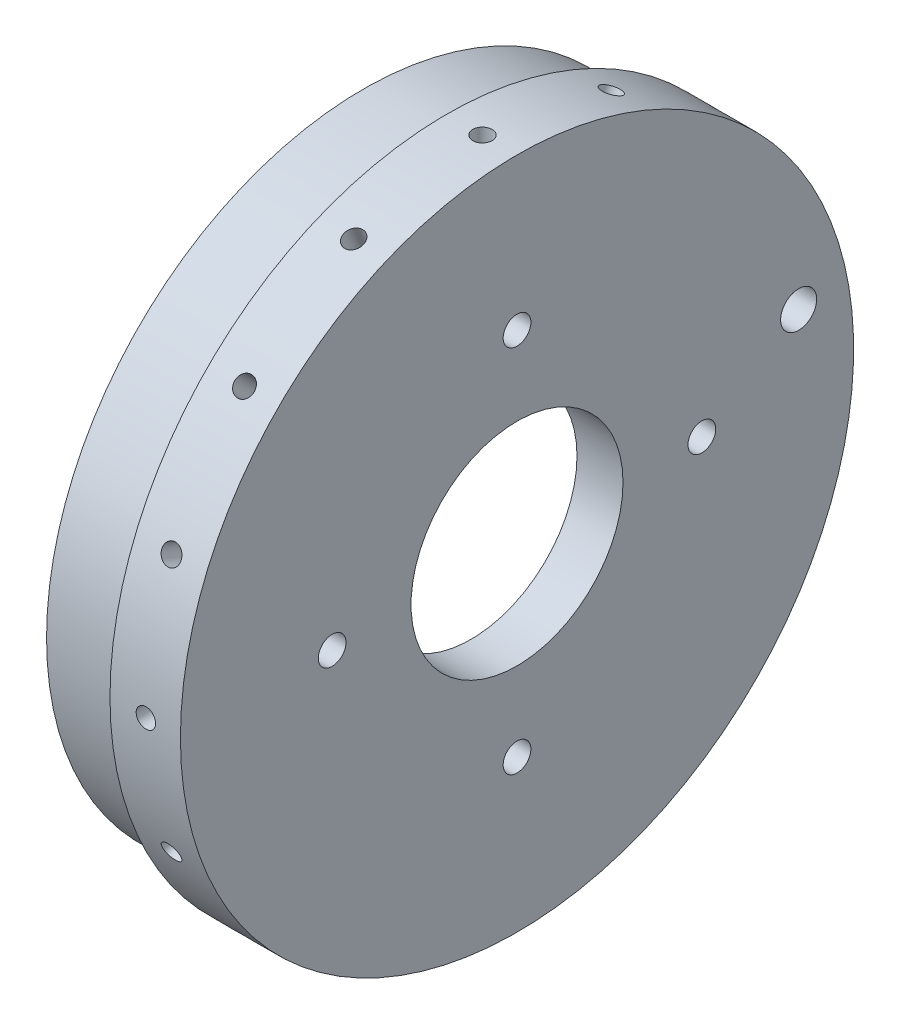
SolidWorks part; units mm, degrees
material "6061 Alloy"
ref_plane "Front Plane" through (0, 0, 0) normal (0, 0, 1) x (1, 0, 0)
ref_plane "Top Plane" through (0, 0, 0) normal (0, 1, 0) x (1, 0, 0)
ref_plane "Right Plane" through (0, 0, 0) normal (1, 0, 0) x (0, 0, -1)
sketch "Sketch4" plane through (0, 0, 0) normal (0, 0, 1) x (1, 0, 0)
  line L0 (0, 0) -> (0, 57.15)
  line L1 (0, 57.15) -> (34.225, 57.15)
  line L2 (34.225, 57.15) -> (34.225, 60.706)
  line L3 (34.225, 60.706) -> (46.925, 60.706)
  line L14 (46.925, 60.706) -> (46.925, 0)
  line L15 (0, 0) -> (46.925, 0)
  dimension "D2" = 34.225
  dimension "D5" = 12.7
  dimension "D6" = 57.15
  dimension "D1" = 60.706
revolve "Revolve1" add sketch "Sketch4" angle 360 about L15
hole_wizard "#6-32 Tapped Hole1" positions "3DSketch4" profile "Sketch5" tap size "#6-32" standard "ANSI Inch"
sketch3d "3DSketch4"
  line L0 (40.702, 0, 60.706) -> (46.925, 0, 60.706) construction
  line L2 (40.702, 0, 60.706) -> (34.225, 0, 60.706) construction
  circle A1 centre (46.925, 0, 0) radius 60.706 construction
  circle A2 centre (34.225, 0, 0) radius 60.706 construction
  point P10 (40.702, 0, 60.706)
  point P18 (-13.781, 0, 0)
  point P24 (-26.481, 0, 0)
  dimension "D1" = 6.477
sketch "Sketch5" plane through (40.702, 0, 60.706) normal (1, 0, 0) x (0, -1, 0)
  line L0 (0, 0) -> (0, 13.5127)
  line L1 (0, 13.5127) -> (1.3525, 12.7)
  line L2 (1.3525, 12.7) -> (1.3525, 10.16)
  line L3 (1.3525, 10.16) -> (1.7526, 10.16)
  line L4 (1.7526, 10.16) -> (1.7526, 0)
  line L5 (1.7526, 0) -> (0, 0)
  line L10 (0, 13.5127) -> (-1.3526, 12.7) construction
  line L11 (0, -6.35) -> (0, 107.95) construction
  dimension "Tap Drill Dia." = 2.7051
  dimension "Tap Drill Depth" = 12.7
  dimension "Thread Major Dia." = 3.5052
  dimension "Thread Depth" = 10.16
  dimension "Drill Angle" = 118
pattern_circular "CirPattern3" count 16 over 360 about axis through (0, 0, 0) along (1, 0, 0) of "#6-32 Tapped Hole1"
sketch "Sketch6" plane through (0, 0, 0) normal (-1, 0, 0) x (0, 0, 1)
  circle A0 centre (0, 0) radius 57.15
extrude "Cut-Extrude1" cut sketch "Sketch6" against normal blind 19.23 contours A0
sketch "Sketch7" plane through (46.925, 0, 0) normal (1, 0, 0) x (0, 0, -1)
  line L0 (16.805, -1010.8221) -> (16.805, 48989.1779) construction
  line L1 (16.805, 21.05) -> (-16.805, 21.05)
  line L2 (21.05, 16.805) -> (21.05, -16.805)
  line L3 (16.805, -21.05) -> (-16.805, -21.05)
  line L4 (-21.05, 16.805) -> (-21.05, -16.805)
  line L5 (21.05, 21.05) -> (-21.05, -21.05) construction
  line L6 (21.05, -21.05) -> (-21.05, 21.05) construction
  line L7 (0, -1000) -> (0, 49000) construction
  line L8 (-16.805, -1002.9393) -> (-16.805, 48997.0607) construction
  line L9 (-21.05, 0) -> (49000, 0) construction
  line L10 (-21.05, 16.805) -> (48969.2707, 16.805) construction
  line L12 (-21.05, 16.805) -> (-16.805, 21.05)
  line L13 (16.805, 21.05) -> (21.05, 16.805)
  line L14 (21.05, -16.805) -> (16.805, -21.05)
  line L15 (-16.805, -21.05) -> (-21.05, -16.805)
  point P0 (0, 0)
  point P30 (0, 0)
  dimension "D1" = 42.1
  dimension "D2" = 42.1
  dimension "D3" = 16.805
  dimension "D4" = 16.805
  dimension "D5" = 16.805
  dimension "D7" = 4
sketch "Sketch8" plane through (46.925, 0, 0) normal (1, 0, 0) x (0, 0, -1)
  circle A0 centre (-15.5, 15.5) radius 2.25
  circle A1 centre (15.5, 15.5) radius 2.25
  circle A2 centre (15.5, -15.5) radius 2.25
  circle A3 centre (-15.5, -15.5) radius 2.25
  circle A4 centre (0, 0) radius 60.706 construction
  circle A5 centre (33.335, 0) radius 2.5
  circle A6 centre (0, -33.335) radius 2.5
  circle A7 centre (-33.335, 0) radius 2.5
  circle A8 centre (0, 33.335) radius 2.5
  point P12 (0, 0)
  point P23 (0, 0)
  dimension "D1" = 15.5
  dimension "D3" = 4.5
  dimension "D4" = 4
  dimension "D6" = 5
  dimension "D2" = 15.5
  dimension "D5" = 33.335
  dimension "D7" = 4
sketch "Sketch9" plane through (46.925, 0, 0) normal (1, 0, 0) x (0, 0, -1)
  circle A0 centre (0, 0) radius 19.1135
  dimension "D1" = 38.227
extrude "Cut-Extrude4" cut sketch "Sketch9" against normal blind 19.23
sketch "Sketch10" plane through (19.23, 0, 0) normal (-1, 0, 0) x (0, 0, 1)
  circle A0 centre (0, 0) radius 47.5063
  dimension "D1" = 95.0127
extrude "Cut-Extrude5" cut sketch "Sketch10" against normal blind 15
sketch "Sketch11" plane through (34.23, 0, 0) normal (-1, 0, 0) x (0, 0, 1)
  circle A0 centre (0, 0) radius 39
  dimension "D1" = 78
extrude "Cut-Extrude6" cut sketch "Sketch11" against normal blind 4.4
hole_wizard "M4x0.7 Tapped Hole1" positions "Sketch12" profile "Sketch13" tap size "M4x0.7" standard "ANSI Metric"
sketch "Sketch12" plane through (34.23, 0, 0) normal (-1, 0, 0) x (0, 0, 1)
  line L0 (8.9822, 40.5163) -> (0, 0) construction
  line L2 (0, 0) -> (0, 43) construction
  circle A0 centre (0, 0) radius 41.5
  point P0 (8.9822, 40.5163)
  dimension "D2" = 83
  dimension "D1" = 12.5
sketch "Sketch13" plane through (34.23, 40.5163, 8.9822) normal (0, 1, 0) x (0, 0, 1)
  line L0 (0, 0) -> (0, 12.4914)
  line L1 (0, 12.4914) -> (1.65, 11.5)
  line L2 (1.65, 11.5) -> (1.65, 8)
  line L3 (1.65, 8) -> (2, 8)
  line L4 (2, 8) -> (2, 0)
  line L5 (2, 0) -> (0, 0)
  line L10 (0, 12.4914) -> (-1.65, 11.5) construction
  line L11 (0, -6.35) -> (0, 107.95) construction
  dimension "Tap Drill Dia." = 3.3
  dimension "Tap Drill Depth" = 11.5
  dimension "Thread Major Dia." = 4
  dimension "Thread Depth" = 8
  dimension "Drill Angle" = 118
pattern_circular "CirPattern4" count 8 over 360 about axis through (0, 0, 0) along (1, 0, 0) of "M4x0.7 Tapped Hole1"
hole_wizard "M3 Clearance Hole1" [suppressed] positions "3DSketch5" profile "Sketch14" hole size "M3" standard "ANSI Metric"
sketch3d "3DSketch5"
  point P0 (46.925, 15.5, -15.5)
  point P3 (46.925, 15.5, 15.5)
  point P6 (46.925, -15.5, -15.5)
  point P9 (46.925, -15.5, 15.5)
sketch "Sketch14" plane through (46.925, 15.5, -15.5) normal (0, 1, 0) x (0, 0, -1)
  line L0 (0, 0) -> (0, 8.295)
  line L1 (0, 8.295) -> (1.8, 8.295)
  line L2 (1.8, 8.295) -> (1.8, 0)
  line L5 (1.8, 0) -> (0, 0)
  line L11 (0, -6.35) -> (0, 107.95) construction
  dimension "Thru Hole Dia." = 3.6
  dimension "Thru Hole Depth" = 8.295
extrude "Cut-Extrude7" cut sketch "Sketch8" against normal blind 10 contours A5
pattern_circular "CirPattern5" count 4 over 360 about axis through (0, 0, 0) along (1, 0, 0) of "Cut-Extrude7"
hole_wizard "M5x0.8 Tapped Hole3" [suppressed] positions "Sketch24" profile "Sketch25" tap size "M5x0.8" standard "ANSI Metric"
sketch "Sketch24" [suppressed] plane through (38.63, 0, 0) normal (-1, 0, 0) x (0, 0, 1)
  point P0 (-33.335, 0)
  point P3 (0, 33.335)
  point P6 (33.335, 0)
  point P9 (0, -33.335)
sketch "Sketch25" plane through (38.63, 0, -33.335) normal (0, 1, 0) x (0, 0, 1)
  line L0 (0, 0) -> (0, 8.295)
  line L1 (0, 8.295) -> (2.1, 8.295)
  line L2 (2.1, 8.295) -> (2.1, 0)
  line L5 (2.1, 0) -> (0, 0)
  line L11 (0, -6.35) -> (0, 107.95) construction
  dimension "Thru Tap Drill Dia." = 4.2
  dimension "Thru Tap Drill Depth" = 8.295
cosmetic thread "Hole Thread1" [suppressed] parameters "D2"=5
cosmetic thread "Hole Thread2" [suppressed] parameters "D2"=5
cosmetic thread "Hole Thread3" [suppressed] parameters "D2"=5
cosmetic thread "Hole Thread4" [suppressed] parameters "D2"=5
sketch "Sketch26" plane through (19.23, 0, 0) normal (-1, 0, 0) x (0, 0, 1)
  line L6 (-50.7884, 11.1656) -> (0.0753, 0.3542) construction
  line L7 (0.0753, 0.3542) -> (-51.5666, 0.3542) construction
  circle A8 centre (-50.7884, 11.1656) radius 3.25
  circle A13 centre (0, 0) radius 47.5063 construction
  circle A14 centre (0, 0) radius 47.5063 construction
  circle A15 centre (0, 0) radius 57.15 construction
  circle A16 centre (0, 0) radius 57.15 construction
  dimension "D1" = 6.5
  dimension "D2" = 9.6436
  dimension "D4" = 52
  dimension "D3" = 12
extrude "Cut-Extrude8" cut sketch "Sketch26" against normal up to next
equation "\"D2@Sketch4\"=22.225mm+12"
equation "\"D1@Sketch4\"=4.78in/2"
